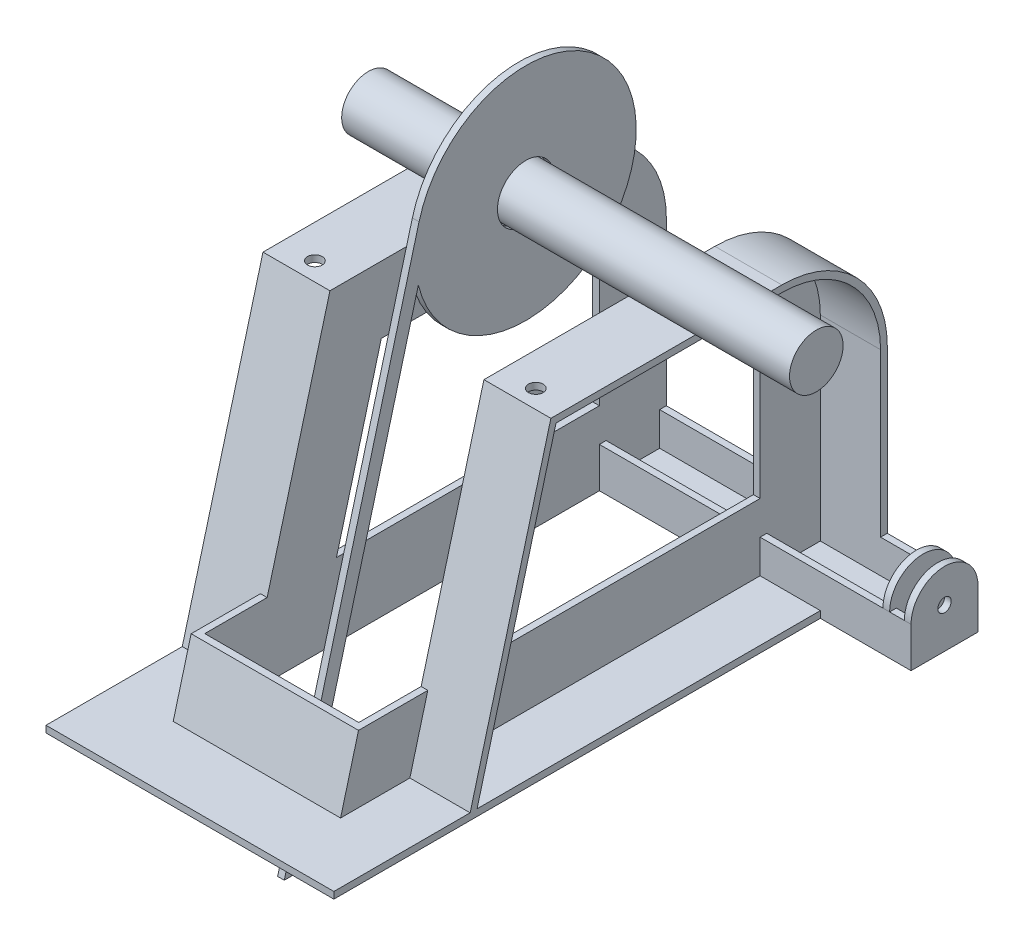
SolidWorks part; units mm, degrees
ref_plane "Front Plane" through (0, 0, 0) normal (0, 0, 1) x (1, 0, 0)
ref_plane "Top Plane" through (0, 0, 0) normal (0, 1, 0) x (1, 0, 0)
ref_plane "Right Plane" through (0, 0, 0) normal (1, 0, 0) x (0, 0, -1)
sketch "Sketch2" plane through (0, 0, 0) normal (0, 0, 1) x (1, 0, 0)
  line L0 (-65, 0) -> (604, 0)
  line L1 (-65, 40) -> (604, 40)
  line L2 (-65, 40) -> (-65, 0)
  line L4 (604, 40) -> (604, 0)
  line L5 (-50, 40) -> (-50, 0) construction
  line L6 (50, 40) -> (50, 0) construction
  line L7 (120, 40) -> (120, 0) construction
  line L8 (210, 40) -> (210, 0) construction
  line L9 (280, 40) -> (280, 0) construction
  line L10 (380, 40) -> (380, 0) construction
  line L11 (400, 40) -> (400, 0) construction
  line L12 (589, 40) -> (589, 0) construction
  line L13 (0, 40) -> (0, 0) construction
  line L14 (330, 40) -> (330, 0) construction
  line L15 (165, 40) -> (165, 0) construction
  line L16 (494.5, 40) -> (494.5, 0) construction
  point P29 (0, 0)
  point P30 (178.2255, 0)
  point P31 (662.9793, 0)
  point P32 (509.0372, 0)
  point P33 (0, 0)
  dimension "D1" = 40
  dimension "D3" = 90
  dimension "D4" = 100
  dimension "D5" = 15
  dimension "D6" = 189
  dimension "D7" = 100
  dimension "D2" = 330
  dimension "D8" = 20
  dimension "D9" = 15
revolve "Revolve1" add sketch "Sketch2" angle 360 about L0
sketch "Sketch4" plane through (0, 0, 0) normal (0, 0, 1) x (1, 0, 0)
  line L0 (0, 0) -> (0, -100) construction
  line L1 (0, -100) -> (-50000, -100) construction
  line L2 (330, 0) -> (330, -100) construction
  point P5 (0, -177.5102)
  dimension "D1" = 100
ref_plane "Plane2" through (0, -100, 0) normal (0, 1, 0) x (1, 0, 0)
sketch "Sketch3" plane through (0, -100, 0) normal (0, 1, 0) x (1, 0, 0)
  line L0 (165, 0) -> (165, -50000) construction
  line L1 (-50, -172.5) -> (50, -172.5)
  line L2 (-50, -172.5) -> (-50, 172.5)
  line L3 (-50, 172.5) -> (50, 172.5)
  line L4 (50, -172.5) -> (50, 172.5)
  line L5 (-50, -172.5) -> (50, 172.5) construction
  line L6 (-50, 172.5) -> (50, -172.5) construction
  line L8 (380, 172.5) -> (280, 172.5)
  line L9 (280, -172.5) -> (280, 172.5)
  line L10 (380, -172.5) -> (280, -172.5)
  line L11 (380, -172.5) -> (380, 172.5)
  point P0 (0, 0)
  point P13 (0, 0)
  point P14 (0, 0)
  point P15 (0, 0)
  point P16 (0, 0)
  point P17 (0, 0)
  point P18 (0, 0)
  point P19 (0, 0)
  point P20 (0, 0)
  point P21 (0, 0)
  dimension "D1" = 100
  dimension "D2" = 345
ref_plane "Plane3" through (494.5, 0, 0) normal (1, 0, 0) x (0, 0, -1)
sketch "Sketch5" plane through (494.5, 0, 0) normal (1, 0, 0) x (0, 0, -1)
  line L0 (0, 0) -> (280, 0) construction
  line L9 (280, 0) -> (280, -500) construction
  circle A0 centre (280, -500) radius 10 construction
  point P4 (0, 0)
  point P5 (226.5354, 0)
  dimension "D3" = 20
  dimension "D2" = 500
  dimension "D1" = 280
sketch "Sketch6" plane through (494.5, 0, 0) normal (1, 0, 0) x (0, 0, -1)
  line L3 (230, -500) -> (230, -550)
  line L4 (230, -550) -> (280, -550)
  line L5 (280, -550) -> (330, -550)
  line L6 (330, -550) -> (330, -500)
  circle A0 centre (280, -500) radius 10
  circle A1 centre (280, -500) radius 10 construction
  arc A3 (330, -500) -> (230, -500) centre (280, -500) ccw
  dimension "D1" = 100
extrude "Boss-Extrude1" add sketch "Sketch6" along normal mid plane 42 separate body
sketch "Sketch7" plane through (625, 0, 0) normal (0, -1, 0) x (-1, 0, 0)
  line L0 (130.5, 290) -> (130.5, 270) construction
  line L6 (119.5, 205) -> (141.5, 205)
  line L8 (119.5, 205) -> (119.5, 355)
  line L9 (119.5, 355) -> (141.5, 355)
  line L10 (141.5, 205) -> (141.5, 355)
  line L11 (119.5, 205) -> (141.5, 355) construction
  line L12 (119.5, 355) -> (141.5, 205) construction
  point P0 (130.5, 280)
  point P1 (130.5, 280)
  dimension "D1" = 22
  dimension "D2" = 150
extrude "Cut-Extrude1" cut sketch "Sketch7" against normal through all both and the other way through all
ref_plane "Plane4" through (50, 0, 0) normal (1, 0, 0) x (0, 0, -1)
ref_plane "Plane9" through (165, 0, 0) normal (1, 0, 0) x (0, 0, -1)
sketch "Sketch20" plane through (165, 0, 0) normal (1, 0, 0) x (0, 0, -1)
  line L0 (-159.3778, 42.7051) -> (-360.6579, -708.4824)
  line L1 (-360.6579, -708.4824) -> (-339.9523, -708.4824)
  line L2 (-339.9523, -708.4824) -> (-160.4387, -38.5283)
  arc A0 (-160.4387, -38.5283) -> (-159.3778, 42.7051) centre (0, 0) ccw
  circle A1 centre (0, 0) radius 42.2992
  point P1 (-339.9523, -708.4824)
  dimension "D1" = 330
  dimension "D2" = 15
  dimension "D3" = 20
  dimension "D4" = 708.4824
sketch "Sketch30" plane through (50, 0, 0) normal (1, 0, 0) x (0, 0, -1)
  line L0 (172.5, -100) -> (122.5, -100)
  line L1 (200000, -100) -> (-250000, -100) construction
  line L2 (330, -500) -> (330, -100) construction
  line L3 (330, -257.5) -> (330, -500)
  line L4 (172.5, -100) -> (-172.5, -100) construction
  line L7 (330, -550) -> (330, -500)
  line L8 (122.5, -100) -> (-172.5, -100)
  line L9 (-172.5, -100) -> (172.5, -100) construction
  line L10 (-172.5, -100) -> (-266.2822, -450)
  line L11 (-293.0771, -550) -> (330, -550) construction
  line L12 (230, -550) -> (230, -500)
  line L13 (230, -257.5) -> (230, -450)
  line L14 (172.5, -200) -> (122.5, -200)
  line L15 (122.5, -200) -> (-95.7673, -200)
  line L16 (-95.7673, -200) -> (-162.7546, -450)
  line L17 (-293.0771, -550) -> (-189.5495, -550)
  line L18 (230, -550) -> (330, -550)
  line L19 (230, -500) -> (230, -550) construction
  line L20 (-396.6048, -550) -> (-369.8098, -450)
  line L21 (330, -550) -> (-396.6048, -550)
  line L22 (330, -550) -> (330, -257.5)
  line L23 (230, -450) -> (-162.7546, -450)
  line L24 (-396.6048, -550) -> (-396.6048, -450) construction
  line L26 (-172.5, -100) -> (-293.0771, -550) construction
  line L27 (-266.2822, -450) -> (-396.6048, -450)
  line L28 (-95.7673, -200) -> (-196.4846, -575.8819) construction
  line L29 (230, -257.5) -> (230, -500) construction
  arc A0 (330, -257.5) -> (172.5, -100) centre (172.5, -257.5) ccw
  circle A1 centre (280, -500) radius 50 construction
  circle A2 centre (280, -500) radius 50 construction
  arc A4 (230, -257.5) -> (172.5, -200) centre (172.5, -257.5) ccw
  point P35 (-468.3223, -550)
  point P42 (330, -396.832)
  point P43 (330, -252.8045)
  dimension "D2" = 15
  dimension "D1" = 50
  dimension "D3" = 100
extrude "Boss-Extrude12" add sketch "Sketch30" against normal blind 10 separate body contours A4 L13 L12 L18 L7 L3 A0 L0 L8 L10 L17 L16 L15 L14
sketch "Sketch31" plane through (40, 0, 0) normal (-1, 0, 0) x (0, 0, 1)
  line L0 (293.0771, -550) -> (172.5, -100)
  line L1 (172.5, -100) -> (-172.5, -100)
  line L2 (-330, -257.5) -> (-330, -550)
  line L3 (-330, -550) -> (396.6048, -550) construction
  line L4 (172.5, -100) -> (266.2822, -450) construction
  arc A1 (-172.5, -100) -> (-330, -257.5) centre (-172.5, -257.5) ccw
extrude "Extrude-Thin8" add sketch "Sketch31" along normal up to vertex (90 mm away) thin up to point (-50, -100, 172.5) thin type one direction reverse wall 10
mirror "Mirror8" about plane through (165, 0, 0) normal (1, 0, 0) of bodies 140
sketch "Sketch34" plane through (515.5, 0, 0) normal (1, 0, 0) x (0, 0, -1)
  line L0 (230, -500) -> (230, -550)
  line L3 (330, -550) -> (330, -500)
  line L5 (330, -550) -> (-396.6048, -550) construction
  line L6 (230, -550) -> (330, -550) construction
  point P2 (0, 0)
  point P5 (230, -550)
extrude "Extrude-Thin9" add sketch "Sketch34" against normal up to surface (475.5 mm away) thin
sketch "Sketch36" plane through (0, -550, 0) normal (0, -1, 0) x (-1, 0, 0)
  line L0 (-280, 230) -> (-50, 230)
  line L9 (-280, -396.6048) -> (-280, 230)
  line L20 (-515.5, 330) -> (50, 330) construction
  line L21 (-280, 330) -> (-380, 330)
  line L22 (-380, 230) -> (-380, -496.6048)
  line L23 (-380, -496.6048) -> (50, -496.6048)
  line L24 (50, -496.6048) -> (50, 330)
  line L25 (50, 330) -> (-50, 330)
  line L26 (-50, 230) -> (-50, -396.6048)
  line L27 (-50, -396.6048) -> (-280, -396.6048)
  line L28 (-165, -396.6048) -> (-165, -496.6048) construction
  line L29 (-50, 330) -> (-280, 330)
  line L30 (-380, 330) -> (-515.5, 330)
  line L31 (-515.5, 330) -> (-515.5, 230)
  line L32 (-515.5, 230) -> (-380, 230)
  line L33 (-515.5, 230) -> (-290, 230) construction
  point P19 (0, 0)
  point P20 (0, 0)
  point P21 (-280, 330)
  point P22 (-380, 330)
  point P23 (-50, 330)
  point P24 (-50, 330)
  point P25 (0, 0)
  point P28 (0, 0)
extrude "Boss-Extrude13" add sketch "Sketch36" along normal blind 10
sketch "Sketch37" plane through (290, 0, 0) normal (1, 0, 0) x (0, 0, -1)
  line L15 (-369.8098, -450) -> (-396.6048, -550)
  line L16 (-396.6048, -550) -> (-396.6048, -560)
  line L17 (-396.6048, -560) -> (-388.9315, -560)
  line L18 (-396.6048, -550) -> (-369.8098, -450) construction
  line L19 (-388.9315, -560) -> (-359.4571, -450)
  line L20 (-396.6048, -560) -> (230, -560) construction
  line L21 (-266.2822, -450) -> (-369.8098, -450) construction
  line L22 (-359.4571, -450) -> (-369.8098, -450)
  dimension "D1" = 10
extrude "Boss-Extrude14" add sketch "Sketch37" along normal up to surface (250 mm away)
sketch "Sketch38" plane through (0, -100, 0) normal (0, 1, 0) x (1, 0, 0)
  line L0 (330, 145) -> (330, -145) construction
  line L1 (0, 145) -> (0, -145) construction
  line L2 (0, 0) -> (330, 0) construction
  line L3 (330, 145) -> (330, 172.5) construction
  line L4 (380, 172.5) -> (280, 172.5) construction
  line L5 (165, 0) -> (165, 330) construction
  line L6 (50, 330) -> (280, 330) construction
  circle A0 centre (0, 145) radius 11
  circle A1 centre (0, -145) radius 11
  circle A2 centre (330, 145) radius 11
  circle A3 centre (330, -145) radius 11
  point P24 (0, 0)
  point P25 (165, 330)
  dimension "D1" = 22
  dimension "D2" = 290
extrude "Cut-Extrude3" cut sketch "Sketch38" against normal blind 10
extrude "Boss-Extrude15" add sketch "Sketch20" along normal mid plane 10 separate body
equation "\"D\"=80"
equation "\"SL\"=500"
equation "\"D1@Sketch2\"=\"D\"/2"
equation "\"Pbw\"= 100"
equation "\"Spw\"=90"
equation "\"D3@Sketch2\"=\"Spw\""
equation "\"Pbs\"=330"
equation "\"D4@Sketch2\"=\"Pbw\""
equation "\"Eclr\"=15"
equation "\"D5@Sketch2\"=\"Eclr\""
equation "\"Gbw\"=189"
equation "\"D7@Sketch2\"=\"Pbw\""
equation "\"Clr\"=20"
equation "\"D8@Sketch2\"=\"Clr\""
equation "\"D6@Sketch2\"=\"Gbw\""
equation "\"D9@Sketch2\"=\"Eclr\""
equation "\"D2@Sketch2\"=\"Pbs\""
equation "\"Pbwb\"=100"
equation "\"D1@Sketch3\"=\"Pbwb\""
equation "\"Pbl\"=345"
equation "\"D2@Sketch3\"=\"Pbl\""
equation "\"Pbh1\"=100"
equation "\"D1@Sketch4\"=\"Pbh1\""
equation "\"Tad\"=280"
equation "\"Taext\"=500"
equation "\"D2@Sketch5\"=\"Taext\""
equation "\"D1@Sketch5\"=\"Tad\""
